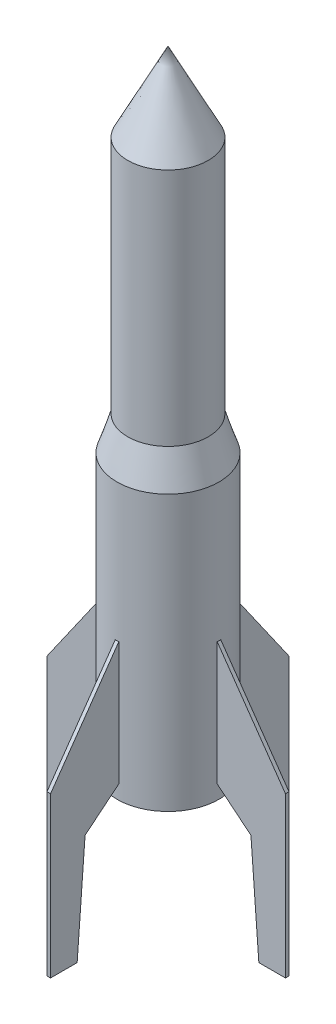
SolidWorks part; units mm, degrees
material "Carcasa cohete"
ref_plane "Alzado" through (0, 0, 0) normal (0, 0, 1) x (1, 0, 0)
ref_plane "Planta" through (0, 0, 0) normal (0, 1, 0) x (1, 0, 0)
ref_plane "Vista lateral" through (0, 0, 0) normal (1, 0, 0) x (0, 0, -1)
sketch "Croquis1" plane through (0, 0, 0) normal (0, 1, 0) x (1, 0, 0)
  circle A0 centre (0, 0) radius 57.5
  dimension "D1" = 115
extrude "Saliente-Extruir1" add sketch "Croquis1" along normal blind 310
sketch "Croquis3" plane through (0, 0, 0) normal (0, -1, 0) x (1, 0, 0)
  circle A0 centre (0, 0) radius 53.5
  circle A1 centre (0, 0) radius 57.5 construction
  dimension "D1" = 4
extrude "Cortar-Extruir1" cut sketch "Croquis3" against normal blind 310
sketch "Croquis4" plane through (0, 0, 0) normal (0, 0, 1) x (1, 0, 0)
  line L0 (0, 0) -> (0, 527.736) construction
  line L1 (0, 310) -> (0, 0) construction
  line L2 (53.5, 310) -> (57.5, 310)
  line L3 (57.5, 310) -> (-57.5, 310) construction
  line L4 (57.5, 310) -> (45.4318, 348.1361)
  line L5 (45.4318, 348.1361) -> (41.4318, 348.1361)
  line L6 (41.4318, 348.1361) -> (53.5, 310)
  dimension "D1" = 4
  dimension "D2" = 40
revolve "Revolución1" add sketch "Croquis4" angle 360 about L0
sketch "Croquis5" plane through (0, 348.1361, 0) normal (0, 1, 0) x (1, 0, 0)
  circle A0 centre (0, 0) radius 45.4318
extrude "Saliente-Extruir2" add sketch "Croquis5" along normal blind 270
sketch "Croquis6" plane through (0, 618.1361, 0) normal (0, 1, 0) x (1, 0, 0)
  circle A0 centre (0, 0) radius 41.4318
  circle A1 centre (0, 0) radius 45.4318 construction
  dimension "D1" = 4
extrude "Cortar-Extruir2" cut sketch "Croquis6" against normal blind 270
sketch "Croquis7" plane through (0, 0, 0) normal (0, 0, 1) x (1, 0, 0)
  line L0 (0, 0) -> (0, 951.3088) construction
  line L1 (0, 707.22) -> (45.4318, 618.1361)
  line L2 (45.4318, 618.1361) -> (43.3919, 618.1361)
  line L3 (41.4318, 618.1361) -> (-41.4318, 618.1361) construction
  line L4 (43.3919, 618.1361) -> (0, 703.22)
  line L5 (0, 703.22) -> (0, 707.22)
  dimension "D1" = 100
  dimension "D2" = 4
revolve "Revolución2" add sketch "Croquis7" angle 360 about L0
ref_plane "Plano1" through (57.5, 0, 0) normal (1, 0, 0) x (0, 0, -1)
sketch "Croquis8" plane through (57.5, 0, 0) normal (1, 0, 0) x (0, 0, -1)
  line L0 (-2, -135) -> (2, -135)
  line L1 (2, -135) -> (2, 155)
  line L2 (2, 155) -> (-2, 155)
  line L3 (-2, 155) -> (-2, -135)
  line L4 (-57.5, 0) -> (57.5, 0) construction
  point P7 (0, -135)
  point P8 (0, 0)
  dimension "D1" = 290
  dimension "D2" = 4
  dimension "D3" = 135
extrude "Saliente-Extruir3" add sketch "Croquis8" along normal blind 77 separate body contours L1 L2 L3 L0
sketch "Croquis9" plane through (0, 0, -2) normal (0, 0, -1) x (-1, 0, 0)
  line L0 (-134.5, -135) -> (-104.5, -135)
  line L1 (-134.5, -135) -> (-57.5, -135) construction
  line L2 (-104.5, -135) -> (-95.5194, -15)
  line L3 (-95.5194, -15) -> (-57.5, 16.1153)
  line L4 (-57.5, 63.25) -> (-57.5, -63.25) construction
  line L5 (-57.5, 16.1153) -> (-57.5, 155)
  line L6 (-134.5, 155) -> (-57.5, 155) construction
  line L7 (-57.5, 155) -> (-134.5, 45)
  line L8 (-134.5, -135) -> (-134.5, 155) construction
  line L9 (-134.5, 45) -> (-134.5, -135)
  dimension "D1" = 30
  dimension "D2" = 120
sketch "Croquis10" plane through (0, 0, -2) normal (0, 0, -1) x (-1, 0, 0)
  line L0 (-104.5, -135) -> (-95.5194, -15)
  line L1 (-95.5194, -15) -> (-57.5, 16.1153)
  line L2 (-57.5, 16.1153) -> (-57.5, -135)
  line L3 (-57.5, -135) -> (-57.5, 155) construction
  line L4 (-57.5, 63.25) -> (-57.5, -63.25) construction
  line L5 (-57.5, -135) -> (-104.5, -135)
  line L6 (-57.5, 155) -> (-134.5, 155)
  line L7 (-134.5, -135) -> (-134.5, 155) construction
  line L8 (-134.5, 155) -> (-57.5, 155) construction
  line L9 (-134.5, 155) -> (-134.5, 45)
  line L10 (-134.5, 45) -> (-57.5, 155)
extrude "Cortar-Extruir3" cut sketch "Croquis10" against normal blind 77
pattern_circular "MatrizC3" count 4 over 360 about axis through (0, 0, 0) along (0, 1, 0) of bodies 108
